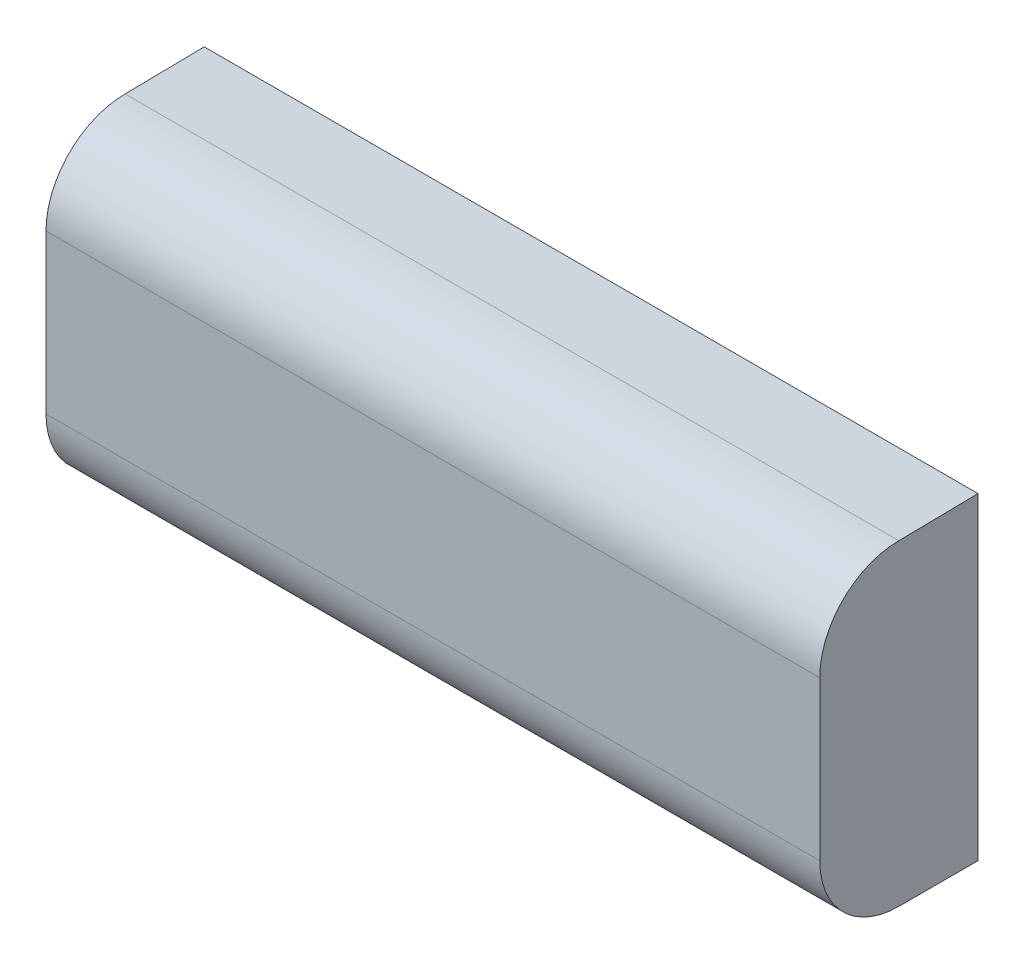
SolidWorks part; units mm, degrees
material "PP homopolímero"
ref_plane "Alzado" through (0, 0, 0) normal (0, 0, 1) x (1, 0, 0)
ref_plane "Planta" through (0, 0, 0) normal (0, 1, 0) x (1, 0, 0)
ref_plane "Vista lateral" through (0, 0, 0) normal (1, 0, 0) x (0, 0, -1)
sketch "Croquis1" plane through (0, 0, 0) normal (1, 0, 0) x (0, 0, -1)
  line L0 (38.1, 44.5141) -> (38.1, 83.2091) construction
  line L5 (38.1, 83.2091) -> (38.1, -75.5508) construction
  line L6 (38.1, 83.2091) -> (0, 82.6141)
  line L7 (-38.1, 44.5141) -> (-38.1, -31.7859)
  line L8 (0, -69.8859) -> (38.1, -69.8859)
  line L9 (38.1, 83.2091) -> (38.1, -69.8859)
  arc A0 (0, 82.6141) -> (-38.1, 44.5141) centre (0, 44.5141) ccw
  arc A1 (-38.1, -31.7859) -> (0, -69.8859) centre (0, -31.7859) ccw
  dimension "D1" = 76.2
  dimension "D2" = 76.2
  dimension "D3" = 76.3
extrude "Saliente-Extruir1" add sketch "Croquis1" along normal blind 372.58
